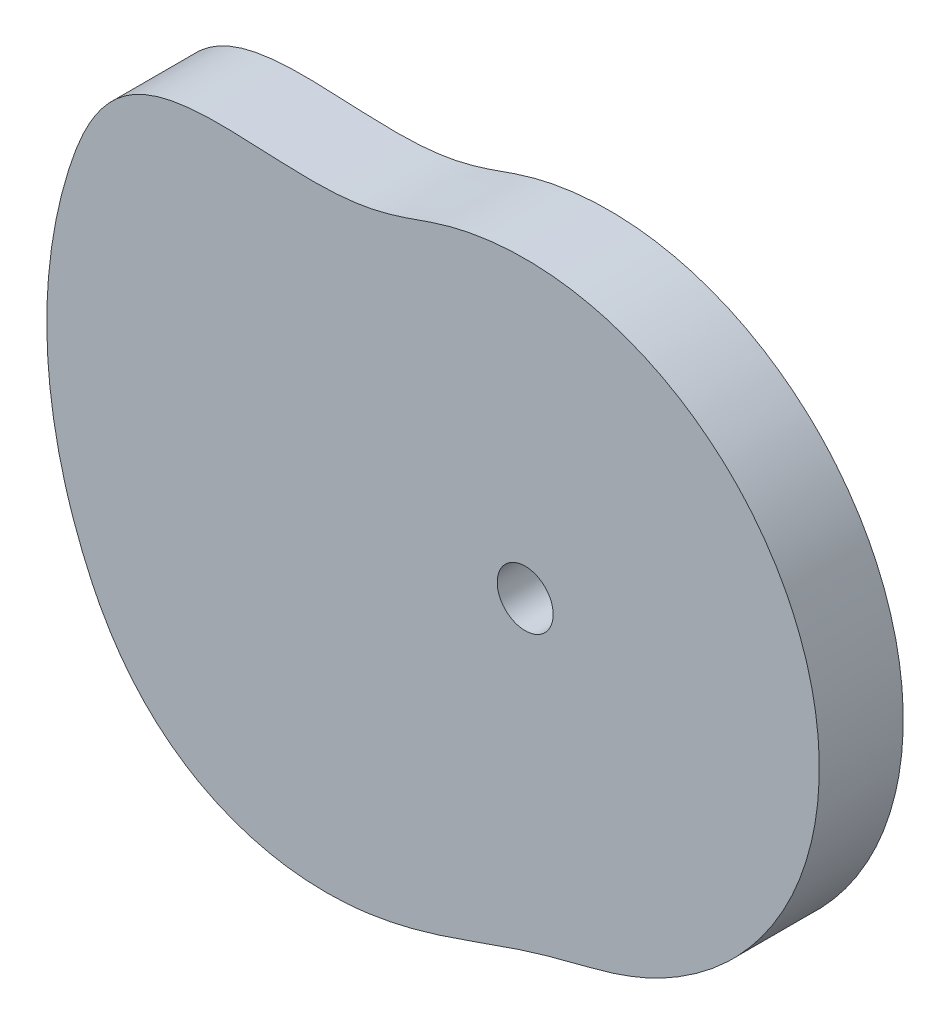
SolidWorks part; units mm, degrees
ref_plane "前视基准面" through (0, 0, 0) normal (0, 0, 1) x (1, 0, 0)
ref_plane "上视基准面" through (0, 0, 0) normal (0, 1, 0) x (1, 0, 0)
ref_plane "右视基准面" through (0, 0, 0) normal (1, 0, 0) x (0, 0, -1)
other "Configuration Table"
curve "曲线1"
sketch "草图1" plane through (0, 0, 0) normal (0, 0, 1) x (1, 0, 0)
  spline S0 degree 3 poles (71.0418, 77.4658) (70.3558, 78.0761) (69.666, 78.6826) (68.9824, 79.2894) (68.2921, 79.893) (67.5889, 80.4787) (66.8917, 81.0727) (66.1815, 81.6527) (65.4592, 82.219) (64.743, 82.7905) (64.018, 83.3518) (63.2913, 83.9128) (62.5525, 84.4601) (61.8092, 84.9989) (61.0716, 85.5435) (60.3217, 86.069) (59.5714, 86.5936) (58.8094, 87.0991) (58.0481, 87.6121) (57.2851, 88.1212) (56.508, 88.6121) (55.7293, 89.0988) (54.9554, 89.5922) (54.1673, 90.0611) (53.3826, 90.531) (52.5876, 90.9916) (51.7924, 91.4509) (50.9918, 91.8999) (50.1906, 92.3439) (49.379, 92.7682) (48.5708, 93.2047) (47.7488, 93.6177) (46.9352, 94.0438) (46.1089, 94.4378) (45.2904, 94.8444) (44.4569, 95.2305) (43.6268, 95.6209) (42.7874, 95.9918) (41.9493, 96.3584) (41.1122, 96.7362) (40.2591, 97.0779) (39.4121, 97.4317) (38.5618, 97.7714) (37.7068, 98.1003) (36.854, 98.4341) (35.9896, 98.7388) (35.127, 99.0509) (34.2637, 99.3642) (33.3894, 99.6483) (32.5216, 99.9416) (31.6489, 100.2237) (30.7694, 100.4879) (29.8934, 100.7648) (29.0097, 101.009) (28.1296, 101.2587) (27.2503, 101.5168) (26.3592, 101.7369) (25.473, 101.9754) (24.5796, 102.1786) (23.6868, 102.3905) (22.7956, 102.6036) (21.8965, 102.7894) (21.0012, 102.9823) (20.1008, 103.1609) (19.1979, 103.3335) (18.2929, 103.4876) (17.391, 103.6523) (16.4876, 103.8023) (15.5807, 103.9413) (14.6708, 104.0724) (13.7598, 104.1888) (12.8507, 104.3123) (11.9405, 104.4215) (11.0305, 104.5214) (10.1172, 104.613) (9.2032, 104.6882) (8.2905, 104.7725) (7.377, 104.8416) (6.4637, 104.9023) (5.5466, 104.9482) (4.6306, 105.006) (3.7132, 105.0277) (2.7968, 105.0626) (1.8801, 105.0824) (0.9633, 105.0878) (0.0467, 105.1062) (-0.87, 105.0875) (-1.7901, 105.0837) (-2.7066, 105.0576) (-3.6238, 105.0463) (-4.5398, 104.9965) (-5.4574, 104.9677) (-6.3728, 104.8937) (-7.2875, 104.8566) (-8.2004, 104.7812) (-9.1132, 104.6985) (-10.0272, 104.6229) (-10.9405, 104.5314) (-11.8505, 104.4315) (-12.7607, 104.3223) (-13.6698, 104.1988) (-14.5808, 104.0824) (-15.4906, 103.951) (-16.3978, 103.8135) (-17.3029, 103.6575) (-18.2078, 103.5135) (-19.1108, 103.3512) (-20.0109, 103.1814) (-20.9111, 103.0022) (-21.8065, 102.8095) (-22.7056, 102.6236) (-23.5968, 102.4105) (-24.4897, 102.1987) (-25.3829, 101.9952) (-26.2694, 101.7577) (-27.1586, 101.5341) (-28.044, 101.2889) (-28.9287, 101.0437) (-29.8068, 100.7806) (-30.6843, 100.5199) (-31.5587, 100.2531) (-32.4344, 99.9698) (-33.3168, 99.677) (-34.2166, 99.3829) (-35.1248, 99.0546) (-36.0548, 98.7408) (-36.9971, 98.4078) (-37.9526, 98.068) (-38.9301, 97.7269) (-39.9227, 97.3781) (-40.933, 97.029) (-41.9582, 96.6747) (-43.003, 96.329) (-44.0658, 95.9773) (-45.1441, 95.6254) (-46.2446, 95.2864) (-47.3643, 94.9549) (-48.5036, 94.6412) (-49.6527, 94.3117) (-50.827, 94.0213) (-52.0087, 93.7108) (-53.217, 93.4512) (-54.4338, 93.1732) (-55.6682, 92.9274) (-56.9187, 92.6963) (-58.1816, 92.4759) (-59.4617, 92.2755) (-60.7527, 92.0989) (-62.0519, 91.9255) (-63.3655, 91.776) (-64.6924, 91.6458) (-66.0297, 91.5387) (-67.3763, 91.4389) (-68.7324, 91.3425) (-70.1032, 91.2897) (-71.4798, 91.2378) (-72.8665, 91.1989) (-74.2598, 91.1654) (-75.6633, 91.1592) (-77.0734, 91.1578) (-78.4934, 91.1697) (-79.9203, 91.1836) (-81.3531, 91.236) (-82.7937, 91.2531) (-84.2399, 91.3124) (-85.6902, 91.3576) (-87.1469, 91.4177) (-88.6063, 91.4938) (-90.0736, 91.5466) (-91.5366, 91.6206) (-93.0033, 91.6902) (-94.4733, 91.7596) (-95.9431, 91.8322) (-97.4133, 91.8898) (-98.88, 91.9494) (-100.3464, 92.0127) (-101.81, 92.0589) (-103.2665, 92.1113) (-104.7164, 92.155) (-106.16, 92.1683) (-107.5966, 92.1918) (-109.0233, 92.2043) (-110.4401, 92.1911) (-111.8434, 92.1715) (-113.237, 92.1438) (-114.6172, 92.0941) (-115.9836, 92.0211) (-117.3341, 91.9447) (-118.6642, 91.844) (-119.9777, 91.7236) (-121.2746, 91.5845) (-122.5548, 91.4243) (-123.8119, 91.2457) (-125.0484, 91.0434) (-126.2625, 90.8263) (-127.4556, 90.584) (-128.6275, 90.3277) (-129.7763, 90.0344) (-130.9037, 89.7263) (-132.0088, 89.3974) (-133.0873, 89.0348) (-134.1478, 88.6553) (-135.1856, 88.2573) (-136.2028, 87.8343) (-137.201, 87.3864) (-138.1774, 86.9077) (-139.1314, 86.4021) (-140.0727, 85.8863) (-140.993, 85.3355) (-141.8907, 84.7544) (-142.7756, 84.1527) (-143.6454, 83.5217) (-144.5011, 82.8673) (-145.3394, 82.1779) (-146.1621, 81.4668) (-146.9698, 80.7169) (-147.7632, 79.9432) (-148.5493, 79.1387) (-149.3172, 78.3023) (-150.0628, 77.4285) (-150.811, 76.5408) (-151.5262, 75.6071) (-152.2369, 74.6474) (-152.9378, 73.6599) (-153.6169, 72.6366) (-154.2859, 71.5858) (-154.9501, 70.5118) (-155.5742, 69.3923) (-156.206, 68.2602) (-156.8177, 67.0973) (-157.4066, 65.9048) (-157.9835, 64.6865) (-158.5593, 63.4471) (-159.1004, 62.1783) (-159.6491, 60.8965) (-160.1635, 59.586) (-160.6737, 58.256) (-161.1775, 56.9084) (-161.6488, 55.5362) (-162.1375, 54.1581) (-162.5935, 52.7555) (-163.0408, 51.3413) (-163.4833, 49.9187) (-163.9098, 48.491) (-164.3366, 47.0604) (-164.7263, 45.619) (-165.1377, 44.1847) (-165.4989, 42.7363) (-165.8716, 41.2913) (-166.2339, 39.8425) (-166.5698, 38.3907) (-166.9056, 36.9394) (-167.2103, 35.4808) (-167.5131, 34.018) (-167.8002, 32.554) (-168.0821, 31.0877) (-168.354, 29.6219) (-168.6009, 28.1507) (-168.8421, 26.6775) (-169.0731, 25.2048) (-169.282, 23.7274) (-169.4809, 22.2506) (-169.6744, 20.7713) (-169.8407, 19.2904) (-170.0027, 17.8073) (-170.1501, 16.3237) (-170.2951, 14.8377) (-170.411, 13.3503) (-170.5211, 11.8603) (-170.6245, 10.3707) (-170.7008, 8.8802) (-170.7721, 7.3902) (-170.8308, 5.9002) (-170.8848, 4.4103) (-170.9099, 2.9201) (-170.9357, 1.4301) (-170.9275, -0.06) (-170.9345, -1.5534) (-170.9146, -3.0469) (-170.8675, -4.5399) (-170.8357, -6.0304) (-170.7699, -7.5201) (-170.7048, -9.0106) (-170.6107, -10.5003) (-170.5126, -11.9871) (-170.4003, -13.4736) (-170.2844, -14.961) (-170.1416, -16.4472) (-169.991, -17.9304) (-169.8344, -19.4113) (-169.6508, -20.8905) (-169.462, -22.3707) (-169.2607, -23.8505) (-169.0552, -25.3284) (-168.8209, -26.8007) (-168.581, -28.2707) (-168.3342, -29.7419) (-168.0606, -31.2107) (-167.783, -32.6779) (-167.4906, -34.1408) (-167.1939, -35.6022) (-166.8722, -37.0579) (-166.5407, -38.5109) (-166.204, -39.9626) (-165.8404, -41.4109) (-165.4733, -42.8584) (-165.0902, -44.3009) (-164.7044, -45.7431) (-164.2894, -47.1765) (-163.8832, -48.6129) (-163.4553, -50.0404) (-162.9976, -51.4592) (-162.5541, -52.8835) (-162.0824, -54.2986) (-161.6, -55.7111) (-161.1161, -57.1212) (-160.5973, -58.519) (-160.0942, -59.924) (-159.561, -61.3183) (-159.0261, -62.7117) (-158.4571, -64.0888) (-157.906, -65.4719) (-157.3199, -66.8414) (-156.7334, -68.2048) (-156.1417, -69.5637) (-155.5345, -70.9118) (-154.9024, -72.2445) (-154.2727, -73.5745) (-153.6211, -74.8889) (-152.9674, -76.2006) (-152.2784, -77.4909) (-151.595, -78.783) (-150.8808, -80.059) (-150.1674, -81.3315) (-149.4179, -82.5808) (-148.6771, -83.8318) (-147.8988, -85.0635) (-147.1165, -86.2919) (-146.3013, -87.4998) (-145.4825, -88.703) (-144.6433, -89.8963) (-143.7713, -91.0701) (-142.8946, -92.2393) (-142.0025, -93.3966) (-141.0808, -94.5327) (-140.1454, -95.6636) (-139.1772, -96.7734) (-138.208, -97.8832) (-137.2003, -98.9633) (-136.1808, -100.0339) (-135.1439, -101.0939) (-134.0801, -102.1337) (-133.0028, -103.1634) (-131.9029, -104.1778) (-130.7694, -105.1598) (-129.6328, -106.1486) (-128.4622, -107.1003) (-127.2813, -108.0478) (-126.0716, -108.9645) (-124.8386, -109.864) (-123.5955, -110.7526) (-122.3298, -111.618) (-121.0377, -112.4535) (-119.7351, -113.2836) (-118.4086, -114.088) (-117.0614, -114.8617) (-115.7027, -115.6272) (-114.3191, -116.3544) (-112.9197, -117.0662) (-111.5005, -117.7513) (-110.074, -118.4304) (-108.6178, -119.0493) (-107.1609, -119.6782) (-105.6823, -120.2645) (-104.1904, -120.8235) (-102.6874, -121.3647) (-101.1764, -121.886) (-99.6468, -122.3649) (-98.1094, -122.8226) (-96.5626, -123.2687) (-94.999, -123.6631) (-93.4319, -124.0413) (-91.8616, -124.4096) (-90.2813, -124.7202) (-88.6967, -125.0289) (-87.1043, -125.2893) (-85.51, -125.5499) (-83.911, -125.7516) (-82.3111, -125.9431) (-80.7115, -126.1151) (-79.1079, -126.256) (-77.5039, -126.3618) (-75.9008, -126.4553) (-74.3037, -126.5165) (-72.7067, -126.5382) (-71.1133, -126.5709) (-69.5233, -126.5383) (-67.9396, -126.5164) (-66.3625, -126.4561) (-64.7931, -126.3605) (-63.2293, -126.2634) (-61.6719, -126.1461) (-60.1222, -125.9941) (-58.583, -125.8202) (-57.051, -125.6481) (-55.5328, -125.43) (-54.0248, -125.2157) (-52.5283, -124.9734) (-51.0426, -124.711) (-49.5641, -124.4468) (-48.0995, -124.1492) (-46.6436, -123.8575) (-45.2067, -123.5297) (-43.7774, -123.2146) (-42.3653, -122.8722) (-40.9601, -122.526) (-39.5736, -122.1489) (-38.1941, -121.7861) (-36.8337, -121.3988) (-35.4795, -121.0266) (-34.1436, -120.6192) (-32.8111, -120.2241) (-31.4961, -119.8117) (-30.1911, -119.4038) (-28.9031, -118.9807) (-27.6227, -118.5618) (-26.3531, -118.1408) (-25.091, -117.7235) (-23.8457, -117.2928) (-22.6098, -116.8604) (-21.3849, -116.4289) (-20.1607, -116.0142) (-18.9528, -115.5814) (-17.7547, -115.1496) (-16.5626, -114.7322) (-15.3798, -114.3104) (-14.205, -113.8886) (-13.0301, -113.4857) (-11.8769, -113.0567) (-10.7197, -112.6609) (-9.5725, -112.2623) (-8.4321, -111.8573) (-7.2923, -111.4729) (-6.1645, -111.0801) (-5.0418, -110.6979) (-3.9223, -110.3331) (-2.812, -109.9573) (-1.6996, -109.6011) (-0.5944, -109.2399) (0.5055, -108.8896) (1.6006, -108.5518) (2.6834, -108.2059) (3.7725, -107.8948) (4.8434, -107.5558) (5.9206, -107.252) (6.9853, -106.9387) (8.0503, -106.6412) (9.1054, -106.3389) (10.1603, -106.0509) (11.2056, -105.7595) (12.2457, -105.4797) (13.2801, -105.2102) (14.307, -104.9413) (15.33, -104.6702) (16.3426, -104.4006) (17.3532, -104.1394) (18.3524, -103.8796) (19.3518, -103.6336) (20.3351, -103.3672) (21.3189, -103.1252) (22.2853, -102.8583) (23.2499, -102.6097) (24.2088, -102.3646) (25.155, -102.0973) (26.0989, -101.8548) (27.0266, -101.5896) (27.9519, -101.3333) (28.8619, -101.0586) (29.7738, -100.806) (30.6647, -100.5168) (31.5563, -100.2563) (32.4341, -99.969) (33.3041, -99.6823) (34.1766, -99.3928) (35.0346, -99.0775) (35.9039, -98.7843) (36.7616, -98.4608) (37.6195, -98.1287) (38.4798, -97.8047) (39.3289, -97.4573) (40.1823, -97.1269) (41.0214, -96.7554) (41.8697, -96.4038) (42.7098, -96.0335) (43.5417, -95.6464) (44.3798, -95.2736) (45.2099, -94.8834) (46.0291, -94.4781) (46.8551, -94.0835) (47.6694, -93.6587) (48.4875, -93.2417) (49.3049, -92.8225) (50.1071, -92.3809) (50.9127, -91.9416) (51.7092, -91.4886) (52.5107, -91.0438) (53.3018, -90.5798) (54.0925, -90.1108) (54.8774, -89.6313) (55.6613, -89.154) (56.4287, -88.658) (57.2061, -88.1728) (57.9643, -87.6597) (58.7359, -87.1621) (59.4876, -86.6413) (60.2426, -86.1203) (60.9925, -85.5901) (61.7379, -85.0517) (62.4817, -84.5135) (63.2092, -83.9589) (63.9426, -83.4101) (64.6713, -82.8526) (65.3922, -82.2794) (66.1087, -81.7025) (66.8186, -81.1224) (67.5226, -80.5398) (68.2222, -79.9492) (68.9217, -79.3524) (69.6091, -78.7427) (70.2885, -78.1284) (70.9765, -77.524) (71.6346, -76.8875) (72.3166, -76.2738) (72.9683, -75.6283) (73.6299, -74.9933) (74.2819, -74.3486) (74.9324, -73.7023) (75.5687, -73.042) (76.2032, -72.3797) (76.8285, -71.7086) (77.4629, -71.0454) (78.0719, -70.3583) (78.6797, -69.6698) (79.2893, -68.9823) (79.8931, -68.2921) (80.4787, -67.5889) (81.0727, -66.8917) (81.6527, -66.1815) (82.219, -65.4592) (82.7905, -64.743) (83.3518, -64.018) (83.9128, -63.2913) (84.4601, -62.5525) (84.9989, -61.8092) (85.5435, -61.0716) (86.069, -60.3217) (86.5936, -59.5714) (87.0991, -58.8094) (87.6121, -58.0481) (88.1212, -57.2851) (88.6121, -56.508) (89.0988, -55.7293) (89.5922, -54.9554) (90.0611, -54.1673) (90.531, -53.3826) (90.9916, -52.5876) (91.4509, -51.7924) (91.8999, -50.9918) (92.3439, -50.1906) (92.7682, -49.379) (93.2047, -48.5708) (93.6177, -47.7488) (94.0438, -46.9352) (94.4378, -46.1089) (94.8444, -45.2904) (95.2305, -44.4569) (95.6209, -43.6268) (95.9918, -42.7874) (96.3584, -41.9493) (96.7362, -41.1122) (97.0779, -40.2591) (97.4317, -39.4121) (97.7714, -38.5618) (98.1004, -37.7068) (98.4337, -36.8539) (98.7413, -35.9871) (99.0465, -35.1221) (99.3667, -34.2613) (99.6479, -33.3893) (99.9417, -32.5217) (100.2237, -31.6488) (100.4879, -30.7694) (100.7649, -29.8934) (101.0087, -29.0096) (101.2607, -28.1269) (101.5132, -27.246) (101.7389, -26.3564) (101.9751, -25.4729) (102.1787, -24.5797) (102.3905, -23.6868) (102.6036, -22.7956) (102.7894, -21.8965) (102.9823, -21.0012) (103.1609, -20.1008) (103.3335, -19.1979) (103.4876, -18.2929) (103.6523, -17.391) (103.8023, -16.4876) (103.9413, -15.5807) (104.0724, -14.6708) (104.1888, -13.7598) (104.3123, -12.8507) (104.4215, -11.9405) (104.5214, -11.0305) (104.613, -10.1172) (104.6882, -9.2032) (104.7725, -8.2905) (104.8416, -7.377) (104.9023, -6.4637) (104.9482, -5.5466) (105.006, -4.6306) (105.0277, -3.7132) (105.0626, -2.7968) (105.0824, -1.8801) (105.0878, -0.9633) (105.1062, -0.0467) (105.0875, 0.87) (105.0837, 1.7901) (105.0576, 2.7066) (105.0463, 3.6238) (104.9965, 4.5398) (104.9677, 5.4574) (104.8937, 6.3728) (104.8566, 7.2875) (104.7812, 8.2004) (104.6985, 9.1132) (104.6229, 10.0272) (104.5314, 10.9405) (104.4315, 11.8505) (104.3223, 12.7607) (104.1988, 13.6698) (104.0824, 14.5808) (103.951, 15.4906) (103.8135, 16.3978) (103.6575, 17.3029) (103.5135, 18.2078) (103.3512, 19.1108) (103.1814, 20.0109) (103.0022, 20.9111) (102.8095, 21.8065) (102.6236, 22.7056) (102.4105, 23.5968) (102.1987, 24.4897) (101.9952, 25.3829) (101.7577, 26.2694) (101.5341, 27.1586) (101.2889, 28.044) (101.0437, 28.9287) (100.7806, 29.8068) (100.5199, 30.6843) (100.2532, 31.5587) (99.9696, 32.4343) (99.6821, 33.304) (99.3929, 34.1767) (99.0775, 35.0346) (98.7843, 35.9039) (98.4608, 36.7616) (98.1287, 37.6195) (97.8047, 38.4798) (97.4573, 39.3289) (97.1269, 40.1823) (96.7554, 41.0214) (96.4038, 41.8697) (96.0335, 42.7098) (95.6464, 43.5417) (95.2736, 44.3798) (94.8834, 45.2099) (94.4781, 46.0291) (94.0835, 46.8551) (93.6587, 47.6694) (93.2417, 48.4875) (92.8225, 49.3049) (92.3809, 50.1071) (91.9416, 50.9127) (91.4886, 51.7092) (91.0438, 52.5107) (90.5798, 53.3018) (90.1108, 54.0925) (89.6313, 54.8774) (89.154, 55.6613) (88.658, 56.4287) (88.1728, 57.2061) (87.6597, 57.9643) (87.1621, 58.7359) (86.6413, 59.4876) (86.1203, 60.2426) (85.5901, 60.9925) (85.0517, 61.7379) (84.5135, 62.4817) (83.9589, 63.2092) (83.4101, 63.9426) (82.8526, 64.6713) (82.2794, 65.3922) (81.7025, 66.1087) (81.1224, 66.8186) (80.5398, 67.5226) (79.9492, 68.2222) (79.3524, 68.9217) (78.7427, 69.6091) (78.1284, 70.2885) (77.524, 70.9765) (76.8875, 71.6346) (76.2738, 72.3166) (75.6283, 72.9683) (74.9933, 73.6299) (74.3486, 74.2819) (73.7023, 74.9324) (73.042, 75.5687) (72.3797, 76.2032) (71.7087, 76.8286) (71.0418, 77.4658) (70.3558, 78.0761) (69.666, 78.6826) knots -0.003364 -0.002246 -0.001128 0 0.001103 0.002222 0.003334 0.004447 0.00556 0.006675 0.007792 0.008908 0.010017 0.011136 0.012257 0.013371 0.014485 0.015601 0.016711 0.017824 0.018937 0.02006 0.02117 0.02229 0.02341 0.024517 0.025634 0.026746 0.027868 0.028984 0.030094 0.031209 0.032324 0.033444 0.034565 0.035674 0.036783 0.037898 0.039024 0.040129 0.041245 0.042361 0.043479 0.044597 0.04571 0.046819 0.047939 0.04905 0.050162 0.051285 0.0524 0.053515 0.054626 0.055745 0.056864 0.057977 0.059089 0.060201 0.061319 0.062437 0.063549 0.06466 0.065784 0.066891 0.068009 0.069125 0.070239 0.071362 0.072474 0.073583 0.074702 0.07582 0.076936 0.078052 0.079167 0.08028 0.081392 0.082515 0.083625 0.084735 0.085856 0.086964 0.088084 0.089204 0.090311 0.09143 0.092548 0.093655 0.094773 0.095892 0.097011 0.098118 0.099237 0.100357 0.101466 0.102586 0.103696 0.104807 0.10593 0.107041 0.108154 0.109269 0.110385 0.111501 0.112619 0.113738 0.114848 0.115969 0.11708 0.118194 0.11931 0.120429 0.121535 0.122659 0.123771 0.124882 0.126 0.127118 0.128227 0.129351 0.130467 0.131571 0.13269 0.133801 0.134928 0.136081 0.137254 0.13845 0.139661 0.1409 0.142149 0.143438 0.144737 0.146048 0.147394 0.148751 0.150132 0.151532 0.152951 0.154391 0.155842 0.157311 0.158803 0.160299 0.161818 0.163356 0.16489 0.166457 0.168032 0.169616 0.17121 0.172813 0.174438 0.176073 0.177706 0.179364 0.181031 0.18271 0.184389 0.186091 0.187794 0.189508 0.191235 0.192973 0.194713 0.196464 0.198228 0.199992 0.201757 0.203546 0.205323 0.207112 0.20889 0.210679 0.21248 0.214257 0.216046 0.217835 0.219611 0.221387 0.223151 0.224902 0.226653 0.228392 0.230106 0.231821 0.233511 0.23519 0.236858 0.238503 0.240124 0.241724 0.243314 0.244882 0.24643 0.247945 0.249452 0.250928 0.252385 0.253828 0.255252 0.256649 0.258033 0.259402 0.260757 0.262087 0.26342 0.264747 0.266052 0.267358 0.268662 0.269963 0.271259 0.272565 0.273883 0.275187 0.276523 0.277848 0.279207 0.280565 0.281951 0.283348 0.284755 0.286185 0.287637 0.289111 0.290602 0.292116 0.293655 0.295207 0.29679 0.298384 0.299999 0.301641 0.303301 0.304984 0.306673 0.308387 0.310118 0.311869 0.313634 0.31541 0.317202 0.319013 0.320821 0.322637 0.324449 0.326266 0.328083 0.329891 0.33171 0.333527 0.335338 0.337146 0.338961 0.340773 0.342595 0.344402 0.34622 0.348033 0.349844 0.351665 0.35347 0.355286 0.3571 0.358912 0.360722 0.362543 0.36435 0.366168 0.367984 0.3698 0.371614 0.373428 0.375241 0.377054 0.378866 0.380678 0.382489 0.384301 0.386125 0.387937 0.38975 0.391563 0.393376 0.395191 0.397007 0.398812 0.400629 0.402449 0.404258 0.406068 0.40788 0.409695 0.411511 0.413328 0.415137 0.416948 0.418761 0.420578 0.422398 0.424208 0.42602 0.427837 0.429646 0.431456 0.433273 0.435093 0.436903 0.438717 0.440538 0.442347 0.444162 0.445973 0.447785 0.449603 0.451414 0.453229 0.455041 0.456853 0.458673 0.460486 0.462297 0.464107 0.465916 0.46773 0.469521 0.471323 0.473123 0.474901 0.47669 0.478474 0.480247 0.482026 0.483806 0.485581 0.487347 0.489119 0.490884 0.492661 0.494432 0.496199 0.49797 0.499752 0.501532 0.503301 0.505082 0.506869 0.508653 0.510454 0.512243 0.514041 0.515846 0.517652 0.519466 0.521282 0.523109 0.524937 0.526777 0.528611 0.530459 0.532313 0.534178 0.536033 0.537905 0.539791 0.541667 0.543563 0.545457 0.547356 0.549264 0.551184 0.553104 0.555026 0.556955 0.558892 0.560827 0.562766 0.564719 0.566657 0.568611 0.570571 0.572529 0.574493 0.576451 0.578411 0.580367 0.58234 0.584297 0.586259 0.588218 0.590174 0.592127 0.594089 0.596038 0.597985 0.599918 0.601864 0.603797 0.605719 0.607641 0.609553 0.611454 0.613356 0.61525 0.617133 0.619007 0.620872 0.622728 0.624563 0.626402 0.628231 0.630041 0.631853 0.633647 0.635417 0.637192 0.638947 0.640696 0.642433 0.64415 0.645855 0.647555 0.649244 0.650925 0.652582 0.654231 0.655869 0.657496 0.659111 0.660718 0.662302 0.663887 0.665455 0.667017 0.668567 0.670101 0.671624 0.673147 0.674654 0.676154 0.677635 0.679115 0.680584 0.682049 0.683503 0.684941 0.686375 0.687798 0.689216 0.690635 0.692039 0.693427 0.694815 0.696185 0.697558 0.698913 0.700267 0.701607 0.702946 0.70427 0.705595 0.706905 0.708199 0.709494 0.710777 0.71206 0.713316 0.714584 0.715826 0.71707 0.7183 0.719521 0.720727 0.721933 0.723131 0.724314 0.725488 0.72665 0.727816 0.728955 0.730101 0.731232 0.732343 0.73347 0.734573 0.735696 0.736804 0.737919 0.739039 0.740159 0.741272 0.742386 0.743497 0.744619 0.745735 0.746845 0.747966 0.749081 0.75019 0.7513 0.75242 0.75354 0.75465 0.75577 0.756881 0.757997 0.759113 0.760224 0.761342 0.762466 0.763579 0.764689 0.765799 0.766922 0.768028 0.769148 0.770257 0.771374 0.772498 0.773611 0.774723 0.775834 0.776953 0.778069 0.779193 0.780308 0.781413 0.782527 0.783648 0.784767 0.785878 0.786989 0.788107 0.789217 0.790335 0.791453 0.792562 0.793679 0.794797 0.795907 0.797025 0.798143 0.799254 0.800374 0.801493 0.802605 0.803718 0.804831 0.805946 0.807063 0.808179 0.809288 0.810407 0.811528 0.812642 0.813756 0.814872 0.815982 0.817095 0.818208 0.819331 0.820441 0.821561 0.822681 0.823788 0.824905 0.826017 0.827139 0.828255 0.829365 0.83048 0.831595 0.832716 0.833836 0.834945 0.836054 0.837169 0.838295 0.8394 0.840516 0.841632 0.84275 0.843868 0.844981 0.84609 0.84721 0.848321 0.849444 0.850556 0.851671 0.852786 0.853897 0.855016 0.856135 0.857248 0.85836 0.859484 0.86059 0.861708 0.86282 0.863931 0.865055 0.866162 0.86728 0.868396 0.86951 0.870633 0.871745 0.872854 0.873973 0.875091 0.876207 0.877323 0.878438 0.879551 0.880663 0.881786 0.882896 0.884006 0.885127 0.886235 0.887355 0.888475 0.889582 0.8907 0.891819 0.892926 0.894044 0.895163 0.896282 0.897389 0.898508 0.899628 0.900737 0.901857 0.902967 0.904078 0.9052 0.906312 0.907425 0.90854 0.909656 0.910772 0.91189 0.913009 0.914119 0.91524 0.916351 0.917465 0.918581 0.919699 0.920806 0.92193 0.923042 0.924153 0.925271 0.926389 0.927498 0.928622 0.929738 0.930842 0.931961 0.933072 0.934199 0.935302 0.936425 0.937533 0.938648 0.939768 0.940888 0.942001 0.943115 0.944226 0.945348 0.946464 0.947574 0.948695 0.94981 0.950919 0.952029 0.953149 0.954269 0.955379 0.956499 0.957609 0.958726 0.959842 0.960953 0.962071 0.963195 0.964308 0.965418 0.966528 0.967651 0.968757 0.969877 0.970986 0.972103 0.973227 0.97434 0.975452 0.976563 0.977682 0.978798 0.979922 0.981037 0.982142 0.983256 0.984377 0.985496 0.986607 0.987718 0.988836 0.989946 0.991064 0.992182 0.993291 0.994408 0.995526 0.996636 0.997754 0.998872 1 1.001103 1.002222 1.003334 only from (70.35, 78.08) to (70.35, 78.08) construction
  spline S1 degree 3 poles (71.0418, 77.4658) (70.3558, 78.0761) (69.666, 78.6826) (68.9824, 79.2894) (68.2921, 79.893) (67.5889, 80.4787) (66.8917, 81.0727) (66.1815, 81.6527) (65.4592, 82.219) (64.743, 82.7905) (64.018, 83.3518) (63.2913, 83.9128) (62.5525, 84.4601) (61.8092, 84.9989) (61.0716, 85.5435) (60.3217, 86.069) (59.5714, 86.5936) (58.8094, 87.0991) (58.0481, 87.6121) (57.2851, 88.1212) (56.508, 88.6121) (55.7293, 89.0988) (54.9554, 89.5922) (54.1673, 90.0611) (53.3826, 90.531) (52.5876, 90.9916) (51.7924, 91.4509) (50.9918, 91.8999) (50.1906, 92.3439) (49.379, 92.7682) (48.5708, 93.2047) (47.7488, 93.6177) (46.9352, 94.0438) (46.1089, 94.4378) (45.2904, 94.8444) (44.4569, 95.2305) (43.6268, 95.6209) (42.7874, 95.9918) (41.9493, 96.3584) (41.1122, 96.7362) (40.2591, 97.0779) (39.4121, 97.4317) (38.5618, 97.7714) (37.7068, 98.1003) (36.854, 98.4341) (35.9896, 98.7388) (35.127, 99.0509) (34.2637, 99.3642) (33.3894, 99.6483) (32.5216, 99.9416) (31.6489, 100.2237) (30.7694, 100.4879) (29.8934, 100.7648) (29.0097, 101.009) (28.1296, 101.2587) (27.2503, 101.5168) (26.3592, 101.7369) (25.473, 101.9754) (24.5796, 102.1786) (23.6868, 102.3905) (22.7956, 102.6036) (21.8965, 102.7894) (21.0012, 102.9823) (20.1008, 103.1609) (19.1979, 103.3335) (18.2929, 103.4876) (17.391, 103.6523) (16.4876, 103.8023) (15.5807, 103.9413) (14.6708, 104.0724) (13.7598, 104.1888) (12.8507, 104.3123) (11.9405, 104.4215) (11.0305, 104.5214) (10.1172, 104.613) (9.2032, 104.6882) (8.2905, 104.7725) (7.377, 104.8416) (6.4637, 104.9023) (5.5466, 104.9482) (4.6306, 105.006) (3.7132, 105.0277) (2.7968, 105.0626) (1.8801, 105.0824) (0.9633, 105.0878) (0.0467, 105.1062) (-0.87, 105.0875) (-1.7901, 105.0837) (-2.7066, 105.0576) (-3.6238, 105.0463) (-4.5398, 104.9965) (-5.4574, 104.9677) (-6.3728, 104.8937) (-7.2875, 104.8566) (-8.2004, 104.7812) (-9.1132, 104.6985) (-10.0272, 104.6229) (-10.9405, 104.5314) (-11.8505, 104.4315) (-12.7607, 104.3223) (-13.6698, 104.1988) (-14.5808, 104.0824) (-15.4906, 103.951) (-16.3978, 103.8135) (-17.3029, 103.6575) (-18.2078, 103.5135) (-19.1108, 103.3512) (-20.0109, 103.1814) (-20.9111, 103.0022) (-21.8065, 102.8095) (-22.7056, 102.6236) (-23.5968, 102.4105) (-24.4897, 102.1987) (-25.3829, 101.9952) (-26.2694, 101.7577) (-27.1586, 101.5341) (-28.044, 101.2889) (-28.9287, 101.0437) (-29.8068, 100.7806) (-30.6843, 100.5199) (-31.5587, 100.2531) (-32.4344, 99.9698) (-33.3168, 99.677) (-34.2166, 99.3829) (-35.1248, 99.0546) (-36.0548, 98.7408) (-36.9971, 98.4078) (-37.9526, 98.068) (-38.9301, 97.7269) (-39.9227, 97.3781) (-40.933, 97.029) (-41.9582, 96.6747) (-43.003, 96.329) (-44.0658, 95.9773) (-45.1441, 95.6254) (-46.2446, 95.2864) (-47.3643, 94.9549) (-48.5036, 94.6412) (-49.6527, 94.3117) (-50.827, 94.0213) (-52.0087, 93.7108) (-53.217, 93.4512) (-54.4338, 93.1732) (-55.6682, 92.9274) (-56.9187, 92.6963) (-58.1816, 92.4759) (-59.4617, 92.2755) (-60.7527, 92.0989) (-62.0519, 91.9255) (-63.3655, 91.776) (-64.6924, 91.6458) (-66.0297, 91.5387) (-67.3763, 91.4389) (-68.7324, 91.3425) (-70.1032, 91.2897) (-71.4798, 91.2378) (-72.8665, 91.1989) (-74.2598, 91.1654) (-75.6633, 91.1592) (-77.0734, 91.1578) (-78.4934, 91.1697) (-79.9203, 91.1836) (-81.3531, 91.236) (-82.7937, 91.2531) (-84.2399, 91.3124) (-85.6902, 91.3576) (-87.1469, 91.4177) (-88.6063, 91.4938) (-90.0736, 91.5466) (-91.5366, 91.6206) (-93.0033, 91.6902) (-94.4733, 91.7596) (-95.9431, 91.8322) (-97.4133, 91.8898) (-98.88, 91.9494) (-100.3464, 92.0127) (-101.81, 92.0589) (-103.2665, 92.1113) (-104.7164, 92.155) (-106.16, 92.1683) (-107.5966, 92.1918) (-109.0233, 92.2043) (-110.4401, 92.1911) (-111.8434, 92.1715) (-113.237, 92.1438) (-114.6172, 92.0941) (-115.9836, 92.0211) (-117.3341, 91.9447) (-118.6642, 91.844) (-119.9777, 91.7236) (-121.2746, 91.5845) (-122.5548, 91.4243) (-123.8119, 91.2457) (-125.0484, 91.0434) (-126.2625, 90.8263) (-127.4556, 90.584) (-128.6275, 90.3277) (-129.7763, 90.0344) (-130.9037, 89.7263) (-132.0088, 89.3974) (-133.0873, 89.0348) (-134.1478, 88.6553) (-135.1856, 88.2573) (-136.2028, 87.8343) (-137.201, 87.3864) (-138.1774, 86.9077) (-139.1314, 86.4021) (-140.0727, 85.8863) (-140.993, 85.3355) (-141.8907, 84.7544) (-142.7756, 84.1527) (-143.6454, 83.5217) (-144.5011, 82.8673) (-145.3394, 82.1779) (-146.1621, 81.4668) (-146.9698, 80.7169) (-147.7632, 79.9432) (-148.5493, 79.1387) (-149.3172, 78.3023) (-150.0628, 77.4285) (-150.811, 76.5408) (-151.5262, 75.6071) (-152.2369, 74.6474) (-152.9378, 73.6599) (-153.6169, 72.6366) (-154.2859, 71.5858) (-154.9501, 70.5118) (-155.5742, 69.3923) (-156.206, 68.2602) (-156.8177, 67.0973) (-157.4066, 65.9048) (-157.9835, 64.6865) (-158.5593, 63.4471) (-159.1004, 62.1783) (-159.6491, 60.8965) (-160.1635, 59.586) (-160.6737, 58.256) (-161.1775, 56.9084) (-161.6488, 55.5362) (-162.1375, 54.1581) (-162.5935, 52.7555) (-163.0408, 51.3413) (-163.4833, 49.9187) (-163.9098, 48.491) (-164.3366, 47.0604) (-164.7263, 45.619) (-165.1377, 44.1847) (-165.4989, 42.7363) (-165.8716, 41.2913) (-166.2339, 39.8425) (-166.5698, 38.3907) (-166.9056, 36.9394) (-167.2103, 35.4808) (-167.5131, 34.018) (-167.8002, 32.554) (-168.0821, 31.0877) (-168.354, 29.6219) (-168.6009, 28.1507) (-168.8421, 26.6775) (-169.0731, 25.2048) (-169.282, 23.7274) (-169.4809, 22.2506) (-169.6744, 20.7713) (-169.8407, 19.2904) (-170.0027, 17.8073) (-170.1501, 16.3237) (-170.2951, 14.8377) (-170.411, 13.3503) (-170.5211, 11.8603) (-170.6245, 10.3707) (-170.7008, 8.8802) (-170.7721, 7.3902) (-170.8308, 5.9002) (-170.8848, 4.4103) (-170.9099, 2.9201) (-170.9357, 1.4301) (-170.9275, -0.06) (-170.9345, -1.5534) (-170.9146, -3.0469) (-170.8675, -4.5399) (-170.8357, -6.0304) (-170.7699, -7.5201) (-170.7048, -9.0106) (-170.6107, -10.5003) (-170.5126, -11.9871) (-170.4003, -13.4736) (-170.2844, -14.961) (-170.1416, -16.4472) (-169.991, -17.9304) (-169.8344, -19.4113) (-169.6508, -20.8905) (-169.462, -22.3707) (-169.2607, -23.8505) (-169.0552, -25.3284) (-168.8209, -26.8007) (-168.581, -28.2707) (-168.3342, -29.7419) (-168.0606, -31.2107) (-167.783, -32.6779) (-167.4906, -34.1408) (-167.1939, -35.6022) (-166.8722, -37.0579) (-166.5407, -38.5109) (-166.204, -39.9626) (-165.8404, -41.4109) (-165.4733, -42.8584) (-165.0902, -44.3009) (-164.7044, -45.7431) (-164.2894, -47.1765) (-163.8832, -48.6129) (-163.4553, -50.0404) (-162.9976, -51.4592) (-162.5541, -52.8835) (-162.0824, -54.2986) (-161.6, -55.7111) (-161.1161, -57.1212) (-160.5973, -58.519) (-160.0942, -59.924) (-159.561, -61.3183) (-159.0261, -62.7117) (-158.4571, -64.0888) (-157.906, -65.4719) (-157.3199, -66.8414) (-156.7334, -68.2048) (-156.1417, -69.5637) (-155.5345, -70.9118) (-154.9024, -72.2445) (-154.2727, -73.5745) (-153.6211, -74.8889) (-152.9674, -76.2006) (-152.2784, -77.4909) (-151.595, -78.783) (-150.8808, -80.059) (-150.1674, -81.3315) (-149.4179, -82.5808) (-148.6771, -83.8318) (-147.8988, -85.0635) (-147.1165, -86.2919) (-146.3013, -87.4998) (-145.4825, -88.703) (-144.6433, -89.8963) (-143.7713, -91.0701) (-142.8946, -92.2393) (-142.0025, -93.3966) (-141.0808, -94.5327) (-140.1454, -95.6636) (-139.1772, -96.7734) (-138.208, -97.8832) (-137.2003, -98.9633) (-136.1808, -100.0339) (-135.1439, -101.0939) (-134.0801, -102.1337) (-133.0028, -103.1634) (-131.9029, -104.1778) (-130.7694, -105.1598) (-129.6328, -106.1486) (-128.4622, -107.1003) (-127.2813, -108.0478) (-126.0716, -108.9645) (-124.8386, -109.864) (-123.5955, -110.7526) (-122.3298, -111.618) (-121.0377, -112.4535) (-119.7351, -113.2836) (-118.4086, -114.088) (-117.0614, -114.8617) (-115.7027, -115.6272) (-114.3191, -116.3544) (-112.9197, -117.0662) (-111.5005, -117.7513) (-110.074, -118.4304) (-108.6178, -119.0493) (-107.1609, -119.6782) (-105.6823, -120.2645) (-104.1904, -120.8235) (-102.6874, -121.3647) (-101.1764, -121.886) (-99.6468, -122.3649) (-98.1094, -122.8226) (-96.5626, -123.2687) (-94.999, -123.6631) (-93.4319, -124.0413) (-91.8616, -124.4096) (-90.2813, -124.7202) (-88.6967, -125.0289) (-87.1043, -125.2893) (-85.51, -125.5499) (-83.911, -125.7516) (-82.3111, -125.9431) (-80.7115, -126.1151) (-79.1079, -126.256) (-77.5039, -126.3618) (-75.9008, -126.4553) (-74.3037, -126.5165) (-72.7067, -126.5382) (-71.1133, -126.5709) (-69.5233, -126.5383) (-67.9396, -126.5164) (-66.3625, -126.4561) (-64.7931, -126.3605) (-63.2293, -126.2634) (-61.6719, -126.1461) (-60.1222, -125.9941) (-58.583, -125.8202) (-57.051, -125.6481) (-55.5328, -125.43) (-54.0248, -125.2157) (-52.5283, -124.9734) (-51.0426, -124.711) (-49.5641, -124.4468) (-48.0995, -124.1492) (-46.6436, -123.8575) (-45.2067, -123.5297) (-43.7774, -123.2146) (-42.3653, -122.8722) (-40.9601, -122.526) (-39.5736, -122.1489) (-38.1941, -121.7861) (-36.8337, -121.3988) (-35.4795, -121.0266) (-34.1436, -120.6192) (-32.8111, -120.2241) (-31.4961, -119.8117) (-30.1911, -119.4038) (-28.9031, -118.9807) (-27.6227, -118.5618) (-26.3531, -118.1408) (-25.091, -117.7235) (-23.8457, -117.2928) (-22.6098, -116.8604) (-21.3849, -116.4289) (-20.1607, -116.0142) (-18.9528, -115.5814) (-17.7547, -115.1496) (-16.5626, -114.7322) (-15.3798, -114.3104) (-14.205, -113.8886) (-13.0301, -113.4857) (-11.8769, -113.0567) (-10.7197, -112.6609) (-9.5725, -112.2623) (-8.4321, -111.8573) (-7.2923, -111.4729) (-6.1645, -111.0801) (-5.0418, -110.6979) (-3.9223, -110.3331) (-2.812, -109.9573) (-1.6996, -109.6011) (-0.5944, -109.2399) (0.5055, -108.8896) (1.6006, -108.5518) (2.6834, -108.2059) (3.7725, -107.8948) (4.8434, -107.5558) (5.9206, -107.252) (6.9853, -106.9387) (8.0503, -106.6412) (9.1054, -106.3389) (10.1603, -106.0509) (11.2056, -105.7595) (12.2457, -105.4797) (13.2801, -105.2102) (14.307, -104.9413) (15.33, -104.6702) (16.3426, -104.4006) (17.3532, -104.1394) (18.3524, -103.8796) (19.3518, -103.6336) (20.3351, -103.3672) (21.3189, -103.1252) (22.2853, -102.8583) (23.2499, -102.6097) (24.2088, -102.3646) (25.155, -102.0973) (26.0989, -101.8548) (27.0266, -101.5896) (27.9519, -101.3333) (28.8619, -101.0586) (29.7738, -100.806) (30.6647, -100.5168) (31.5563, -100.2563) (32.4341, -99.969) (33.3041, -99.6823) (34.1766, -99.3928) (35.0346, -99.0775) (35.9039, -98.7843) (36.7616, -98.4608) (37.6195, -98.1287) (38.4798, -97.8047) (39.3289, -97.4573) (40.1823, -97.1269) (41.0214, -96.7554) (41.8697, -96.4038) (42.7098, -96.0335) (43.5417, -95.6464) (44.3798, -95.2736) (45.2099, -94.8834) (46.0291, -94.4781) (46.8551, -94.0835) (47.6694, -93.6587) (48.4875, -93.2417) (49.3049, -92.8225) (50.1071, -92.3809) (50.9127, -91.9416) (51.7092, -91.4886) (52.5107, -91.0438) (53.3018, -90.5798) (54.0925, -90.1108) (54.8774, -89.6313) (55.6613, -89.154) (56.4287, -88.658) (57.2061, -88.1728) (57.9643, -87.6597) (58.7359, -87.1621) (59.4876, -86.6413) (60.2426, -86.1203) (60.9925, -85.5901) (61.7379, -85.0517) (62.4817, -84.5135) (63.2092, -83.9589) (63.9426, -83.4101) (64.6713, -82.8526) (65.3922, -82.2794) (66.1087, -81.7025) (66.8186, -81.1224) (67.5226, -80.5398) (68.2222, -79.9492) (68.9217, -79.3524) (69.6091, -78.7427) (70.2885, -78.1284) (70.9765, -77.524) (71.6346, -76.8875) (72.3166, -76.2738) (72.9683, -75.6283) (73.6299, -74.9933) (74.2819, -74.3486) (74.9324, -73.7023) (75.5687, -73.042) (76.2032, -72.3797) (76.8285, -71.7086) (77.4629, -71.0454) (78.0719, -70.3583) (78.6797, -69.6698) (79.2893, -68.9823) (79.8931, -68.2921) (80.4787, -67.5889) (81.0727, -66.8917) (81.6527, -66.1815) (82.219, -65.4592) (82.7905, -64.743) (83.3518, -64.018) (83.9128, -63.2913) (84.4601, -62.5525) (84.9989, -61.8092) (85.5435, -61.0716) (86.069, -60.3217) (86.5936, -59.5714) (87.0991, -58.8094) (87.6121, -58.0481) (88.1212, -57.2851) (88.6121, -56.508) (89.0988, -55.7293) (89.5922, -54.9554) (90.0611, -54.1673) (90.531, -53.3826) (90.9916, -52.5876) (91.4509, -51.7924) (91.8999, -50.9918) (92.3439, -50.1906) (92.7682, -49.379) (93.2047, -48.5708) (93.6177, -47.7488) (94.0438, -46.9352) (94.4378, -46.1089) (94.8444, -45.2904) (95.2305, -44.4569) (95.6209, -43.6268) (95.9918, -42.7874) (96.3584, -41.9493) (96.7362, -41.1122) (97.0779, -40.2591) (97.4317, -39.4121) (97.7714, -38.5618) (98.1004, -37.7068) (98.4337, -36.8539) (98.7413, -35.9871) (99.0465, -35.1221) (99.3667, -34.2613) (99.6479, -33.3893) (99.9417, -32.5217) (100.2237, -31.6488) (100.4879, -30.7694) (100.7649, -29.8934) (101.0087, -29.0096) (101.2607, -28.1269) (101.5132, -27.246) (101.7389, -26.3564) (101.9751, -25.4729) (102.1787, -24.5797) (102.3905, -23.6868) (102.6036, -22.7956) (102.7894, -21.8965) (102.9823, -21.0012) (103.1609, -20.1008) (103.3335, -19.1979) (103.4876, -18.2929) (103.6523, -17.391) (103.8023, -16.4876) (103.9413, -15.5807) (104.0724, -14.6708) (104.1888, -13.7598) (104.3123, -12.8507) (104.4215, -11.9405) (104.5214, -11.0305) (104.613, -10.1172) (104.6882, -9.2032) (104.7725, -8.2905) (104.8416, -7.377) (104.9023, -6.4637) (104.9482, -5.5466) (105.006, -4.6306) (105.0277, -3.7132) (105.0626, -2.7968) (105.0824, -1.8801) (105.0878, -0.9633) (105.1062, -0.0467) (105.0875, 0.87) (105.0837, 1.7901) (105.0576, 2.7066) (105.0463, 3.6238) (104.9965, 4.5398) (104.9677, 5.4574) (104.8937, 6.3728) (104.8566, 7.2875) (104.7812, 8.2004) (104.6985, 9.1132) (104.6229, 10.0272) (104.5314, 10.9405) (104.4315, 11.8505) (104.3223, 12.7607) (104.1988, 13.6698) (104.0824, 14.5808) (103.951, 15.4906) (103.8135, 16.3978) (103.6575, 17.3029) (103.5135, 18.2078) (103.3512, 19.1108) (103.1814, 20.0109) (103.0022, 20.9111) (102.8095, 21.8065) (102.6236, 22.7056) (102.4105, 23.5968) (102.1987, 24.4897) (101.9952, 25.3829) (101.7577, 26.2694) (101.5341, 27.1586) (101.2889, 28.044) (101.0437, 28.9287) (100.7806, 29.8068) (100.5199, 30.6843) (100.2532, 31.5587) (99.9696, 32.4343) (99.6821, 33.304) (99.3929, 34.1767) (99.0775, 35.0346) (98.7843, 35.9039) (98.4608, 36.7616) (98.1287, 37.6195) (97.8047, 38.4798) (97.4573, 39.3289) (97.1269, 40.1823) (96.7554, 41.0214) (96.4038, 41.8697) (96.0335, 42.7098) (95.6464, 43.5417) (95.2736, 44.3798) (94.8834, 45.2099) (94.4781, 46.0291) (94.0835, 46.8551) (93.6587, 47.6694) (93.2417, 48.4875) (92.8225, 49.3049) (92.3809, 50.1071) (91.9416, 50.9127) (91.4886, 51.7092) (91.0438, 52.5107) (90.5798, 53.3018) (90.1108, 54.0925) (89.6313, 54.8774) (89.154, 55.6613) (88.658, 56.4287) (88.1728, 57.2061) (87.6597, 57.9643) (87.1621, 58.7359) (86.6413, 59.4876) (86.1203, 60.2426) (85.5901, 60.9925) (85.0517, 61.7379) (84.5135, 62.4817) (83.9589, 63.2092) (83.4101, 63.9426) (82.8526, 64.6713) (82.2794, 65.3922) (81.7025, 66.1087) (81.1224, 66.8186) (80.5398, 67.5226) (79.9492, 68.2222) (79.3524, 68.9217) (78.7427, 69.6091) (78.1284, 70.2885) (77.524, 70.9765) (76.8875, 71.6346) (76.2738, 72.3166) (75.6283, 72.9683) (74.9933, 73.6299) (74.3486, 74.2819) (73.7023, 74.9324) (73.042, 75.5687) (72.3797, 76.2032) (71.7087, 76.8286) (71.0418, 77.4658) (70.3558, 78.0761) (69.666, 78.6826) knots -0.003364 -0.002246 -0.001128 0 0.001103 0.002222 0.003334 0.004447 0.00556 0.006675 0.007792 0.008908 0.010017 0.011136 0.012257 0.013371 0.014485 0.015601 0.016711 0.017824 0.018937 0.02006 0.02117 0.02229 0.02341 0.024517 0.025634 0.026746 0.027868 0.028984 0.030094 0.031209 0.032324 0.033444 0.034565 0.035674 0.036783 0.037898 0.039024 0.040129 0.041245 0.042361 0.043479 0.044597 0.04571 0.046819 0.047939 0.04905 0.050162 0.051285 0.0524 0.053515 0.054626 0.055745 0.056864 0.057977 0.059089 0.060201 0.061319 0.062437 0.063549 0.06466 0.065784 0.066891 0.068009 0.069125 0.070239 0.071362 0.072474 0.073583 0.074702 0.07582 0.076936 0.078052 0.079167 0.08028 0.081392 0.082515 0.083625 0.084735 0.085856 0.086964 0.088084 0.089204 0.090311 0.09143 0.092548 0.093655 0.094773 0.095892 0.097011 0.098118 0.099237 0.100357 0.101466 0.102586 0.103696 0.104807 0.10593 0.107041 0.108154 0.109269 0.110385 0.111501 0.112619 0.113738 0.114848 0.115969 0.11708 0.118194 0.11931 0.120429 0.121535 0.122659 0.123771 0.124882 0.126 0.127118 0.128227 0.129351 0.130467 0.131571 0.13269 0.133801 0.134928 0.136081 0.137254 0.13845 0.139661 0.1409 0.142149 0.143438 0.144737 0.146048 0.147394 0.148751 0.150132 0.151532 0.152951 0.154391 0.155842 0.157311 0.158803 0.160299 0.161818 0.163356 0.16489 0.166457 0.168032 0.169616 0.17121 0.172813 0.174438 0.176073 0.177706 0.179364 0.181031 0.18271 0.184389 0.186091 0.187794 0.189508 0.191235 0.192973 0.194713 0.196464 0.198228 0.199992 0.201757 0.203546 0.205323 0.207112 0.20889 0.210679 0.21248 0.214257 0.216046 0.217835 0.219611 0.221387 0.223151 0.224902 0.226653 0.228392 0.230106 0.231821 0.233511 0.23519 0.236858 0.238503 0.240124 0.241724 0.243314 0.244882 0.24643 0.247945 0.249452 0.250928 0.252385 0.253828 0.255252 0.256649 0.258033 0.259402 0.260757 0.262087 0.26342 0.264747 0.266052 0.267358 0.268662 0.269963 0.271259 0.272565 0.273883 0.275187 0.276523 0.277848 0.279207 0.280565 0.281951 0.283348 0.284755 0.286185 0.287637 0.289111 0.290602 0.292116 0.293655 0.295207 0.29679 0.298384 0.299999 0.301641 0.303301 0.304984 0.306673 0.308387 0.310118 0.311869 0.313634 0.31541 0.317202 0.319013 0.320821 0.322637 0.324449 0.326266 0.328083 0.329891 0.33171 0.333527 0.335338 0.337146 0.338961 0.340773 0.342595 0.344402 0.34622 0.348033 0.349844 0.351665 0.35347 0.355286 0.3571 0.358912 0.360722 0.362543 0.36435 0.366168 0.367984 0.3698 0.371614 0.373428 0.375241 0.377054 0.378866 0.380678 0.382489 0.384301 0.386125 0.387937 0.38975 0.391563 0.393376 0.395191 0.397007 0.398812 0.400629 0.402449 0.404258 0.406068 0.40788 0.409695 0.411511 0.413328 0.415137 0.416948 0.418761 0.420578 0.422398 0.424208 0.42602 0.427837 0.429646 0.431456 0.433273 0.435093 0.436903 0.438717 0.440538 0.442347 0.444162 0.445973 0.447785 0.449603 0.451414 0.453229 0.455041 0.456853 0.458673 0.460486 0.462297 0.464107 0.465916 0.46773 0.469521 0.471323 0.473123 0.474901 0.47669 0.478474 0.480247 0.482026 0.483806 0.485581 0.487347 0.489119 0.490884 0.492661 0.494432 0.496199 0.49797 0.499752 0.501532 0.503301 0.505082 0.506869 0.508653 0.510454 0.512243 0.514041 0.515846 0.517652 0.519466 0.521282 0.523109 0.524937 0.526777 0.528611 0.530459 0.532313 0.534178 0.536033 0.537905 0.539791 0.541667 0.543563 0.545457 0.547356 0.549264 0.551184 0.553104 0.555026 0.556955 0.558892 0.560827 0.562766 0.564719 0.566657 0.568611 0.570571 0.572529 0.574493 0.576451 0.578411 0.580367 0.58234 0.584297 0.586259 0.588218 0.590174 0.592127 0.594089 0.596038 0.597985 0.599918 0.601864 0.603797 0.605719 0.607641 0.609553 0.611454 0.613356 0.61525 0.617133 0.619007 0.620872 0.622728 0.624563 0.626402 0.628231 0.630041 0.631853 0.633647 0.635417 0.637192 0.638947 0.640696 0.642433 0.64415 0.645855 0.647555 0.649244 0.650925 0.652582 0.654231 0.655869 0.657496 0.659111 0.660718 0.662302 0.663887 0.665455 0.667017 0.668567 0.670101 0.671624 0.673147 0.674654 0.676154 0.677635 0.679115 0.680584 0.682049 0.683503 0.684941 0.686375 0.687798 0.689216 0.690635 0.692039 0.693427 0.694815 0.696185 0.697558 0.698913 0.700267 0.701607 0.702946 0.70427 0.705595 0.706905 0.708199 0.709494 0.710777 0.71206 0.713316 0.714584 0.715826 0.71707 0.7183 0.719521 0.720727 0.721933 0.723131 0.724314 0.725488 0.72665 0.727816 0.728955 0.730101 0.731232 0.732343 0.73347 0.734573 0.735696 0.736804 0.737919 0.739039 0.740159 0.741272 0.742386 0.743497 0.744619 0.745735 0.746845 0.747966 0.749081 0.75019 0.7513 0.75242 0.75354 0.75465 0.75577 0.756881 0.757997 0.759113 0.760224 0.761342 0.762466 0.763579 0.764689 0.765799 0.766922 0.768028 0.769148 0.770257 0.771374 0.772498 0.773611 0.774723 0.775834 0.776953 0.778069 0.779193 0.780308 0.781413 0.782527 0.783648 0.784767 0.785878 0.786989 0.788107 0.789217 0.790335 0.791453 0.792562 0.793679 0.794797 0.795907 0.797025 0.798143 0.799254 0.800374 0.801493 0.802605 0.803718 0.804831 0.805946 0.807063 0.808179 0.809288 0.810407 0.811528 0.812642 0.813756 0.814872 0.815982 0.817095 0.818208 0.819331 0.820441 0.821561 0.822681 0.823788 0.824905 0.826017 0.827139 0.828255 0.829365 0.83048 0.831595 0.832716 0.833836 0.834945 0.836054 0.837169 0.838295 0.8394 0.840516 0.841632 0.84275 0.843868 0.844981 0.84609 0.84721 0.848321 0.849444 0.850556 0.851671 0.852786 0.853897 0.855016 0.856135 0.857248 0.85836 0.859484 0.86059 0.861708 0.86282 0.863931 0.865055 0.866162 0.86728 0.868396 0.86951 0.870633 0.871745 0.872854 0.873973 0.875091 0.876207 0.877323 0.878438 0.879551 0.880663 0.881786 0.882896 0.884006 0.885127 0.886235 0.887355 0.888475 0.889582 0.8907 0.891819 0.892926 0.894044 0.895163 0.896282 0.897389 0.898508 0.899628 0.900737 0.901857 0.902967 0.904078 0.9052 0.906312 0.907425 0.90854 0.909656 0.910772 0.91189 0.913009 0.914119 0.91524 0.916351 0.917465 0.918581 0.919699 0.920806 0.92193 0.923042 0.924153 0.925271 0.926389 0.927498 0.928622 0.929738 0.930842 0.931961 0.933072 0.934199 0.935302 0.936425 0.937533 0.938648 0.939768 0.940888 0.942001 0.943115 0.944226 0.945348 0.946464 0.947574 0.948695 0.94981 0.950919 0.952029 0.953149 0.954269 0.955379 0.956499 0.957609 0.958726 0.959842 0.960953 0.962071 0.963195 0.964308 0.965418 0.966528 0.967651 0.968757 0.969877 0.970986 0.972103 0.973227 0.97434 0.975452 0.976563 0.977682 0.978798 0.979922 0.981037 0.982142 0.983256 0.984377 0.985496 0.986607 0.987718 0.988836 0.989946 0.991064 0.992182 0.993291 0.994408 0.995526 0.996636 0.997754 0.998872 1 1.001103 1.002222 1.003334 only from (70.35, 78.08) to (70.35, 78.08)
extrude "凸台-拉伸1" add sketch "草图1" along normal blind 30
sketch "草图2" plane through (0, 0, 0) normal (0, 0, 1) x (1, 0, 0)
  circle A0 centre (0, 0) radius 10
extrude "切除-拉伸1" cut sketch "草图2" along normal blind 30
sketch "草图3" plane through (0, 0, 0) normal (0, 0, 1) x (1, 0, 0)
  point P0 (78.8912, 86.987)
